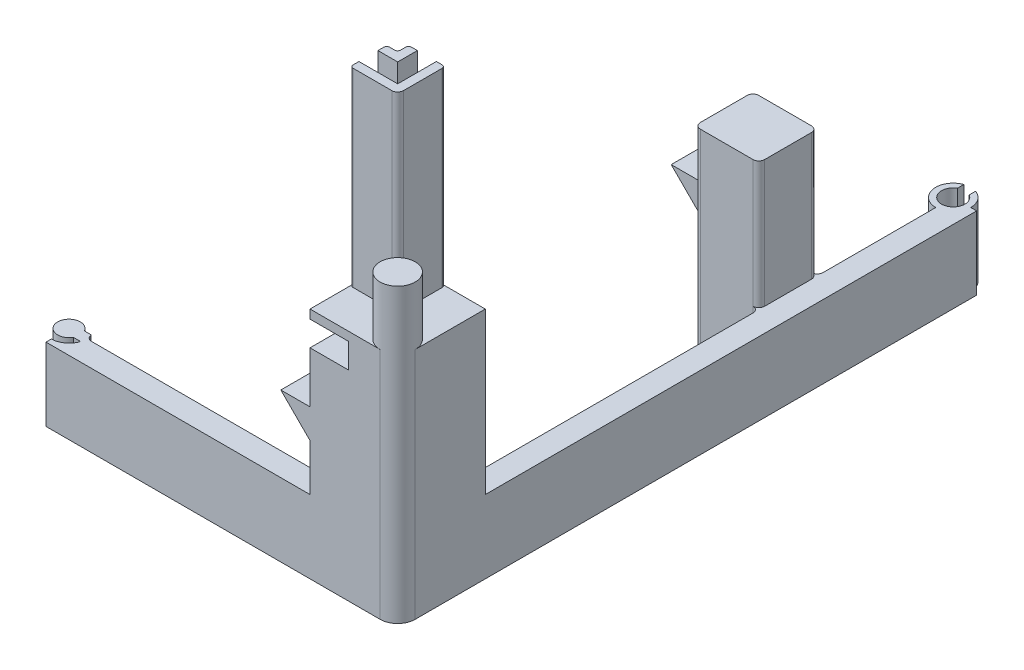
SolidWorks part; units mm, degrees
ref_plane "Front Plane" through (0, 0, 0) normal (0, 0, 1) x (1, 0, 0)
ref_plane "Top Plane" through (0, 0, 0) normal (0, 1, 0) x (1, 0, 0)
ref_plane "Right Plane" through (0, 0, 0) normal (1, 0, 0) x (0, 0, -1)
sketch "Sketch1" plane through (0, 0, 0) normal (0, 1, 0) x (1, 0, 0)
  line L1 (-15, -15) -> (15, -15)
  line L2 (-15, -15) -> (-15, 15)
  line L3 (-15, 15) -> (15, 15)
  line L4 (15, -15) -> (15, 15)
  line L5 (-15, -15) -> (15, 15) construction
  line L6 (-15, 15) -> (15, -15) construction
  point P0 (0, 0)
  dimension "D1" = 30
extrude "Boss-Extrude1" add sketch "Sketch1" along normal blind 80
sketch "Sketch2" plane through (0, 80, 0) normal (0, 1, 0) x (1, 0, 0)
  line L0 (-15, -15) -> (15, -15) construction
  line L1 (15, -15) -> (15, 15) construction
  circle A0 centre (9, -9) radius 6
  dimension "D1" = 12
extrude "Boss-Extrude2" add sketch "Sketch2" along normal blind 20
sketch "Sketch3" plane through (0, 80, 0) normal (0, 1, 0) x (1, 0, 0)
  line L2 (9, -15) -> (15, -15)
  line L4 (15, -15) -> (15, -9)
  circle A1 centre (9, -9) radius 6
  arc A4 (9, -15) -> (15, -9) centre (9, -9) ccw
  dimension "D1" = 0
extrude "Cut-Extrude1" cut sketch "Sketch3" against normal through all
sketch "Sketch4" plane through (0, 80, 0) normal (0, 1, 0) x (1, 0, 0)
  line L16 (-11.25, 1.75) -> (-1.75, 1.75)
  line L17 (-11.25, 11.25) -> (-8.25, 11.25) construction
  line L19 (-11.25, 11.25) -> (-11.25, 8.25) construction
  line L20 (-11.25, 8.25) -> (-8.25, 8.25)
  line L21 (-8.25, 11.25) -> (-8.25, 8.25)
  line L23 (-1.75, 1.75) -> (-1.75, 11.25)
  line L25 (-1.75, 11.25) -> (1.25, 11.25) construction
  line L26 (1.25, 11.25) -> (1.25, -1.25)
  line L27 (1.25, -1.25) -> (-11.25, -1.25)
  line L28 (-11.25, -1.25) -> (-11.25, 1.75) construction
  line L29 (-11.25, 1.75) -> (-11.25, 8.25) construction
  line L30 (-8.25, 11.25) -> (-1.75, 11.25) construction
  line L31 (-11.25, 11.25) -> (-11.25, 15) construction
  line L32 (15, 15) -> (-15, 15) construction
  line L33 (-11.25, 11.25) -> (-15, 11.25) construction
  line L34 (-15, 15) -> (-15, -15) construction
  line L35 (1.25, 11.25) -> (1.25, 15)
  line L36 (1.25, 15) -> (-1.75, 15)
  line L37 (-1.75, 15) -> (-1.75, 11.25)
  line L38 (-11.25, 1.75) -> (-15, 1.75)
  line L39 (-15, 1.75) -> (-15, -1.25)
  line L40 (-15, -1.25) -> (-11.25, -1.25)
  line L41 (-8.25, 11.25) -> (-8.25, 15)
  line L42 (-8.25, 15) -> (-11.25, 15)
  line L43 (-11.25, 15) -> (-11.25, 11.25)
  line L44 (-15, 11.25) -> (-15, 8.25)
  line L45 (-15, 8.25) -> (-11.25, 8.25)
  line L46 (-11.25, 11.25) -> (-15, 11.25)
  dimension "D1" = 6.5
  dimension "D2" = 3
  dimension "D3" = 3.75
extrude "Boss-Extrude3" add sketch "Sketch4" along normal blind 65
sketch "Sketch6" plane through (0, 0, 0) normal (0, -1, 0) x (1, 0, 0)
  line L1 (15, -15) -> (7, -15)
  line L2 (15, -15) -> (15, -183.175)
  line L3 (15, -183.175) -> (13, -183.175)
  line L4 (7, -15) -> (7, -177.175)
  arc A1 (7, -177.175) -> (13, -183.175) centre (7, -183.175) ccw
  dimension "D3" = 12
  dimension "D1" = 168.175
  dimension "D2" = 8
extrude "Boss-Extrude5" add sketch "Sketch6" against normal blind 2
sketch "Sketch7" plane through (0, 2, 0) normal (0, 1, 0) x (1, 0, 0)
  line L0 (7, 187.175) -> (7, 189.175) construction
  line L1 (9, 188.8319) -> (9, 186.6391)
  line L2 (5, 188.8319) -> (5, 186.6391)
  line L3 (7, 179.175) -> (7, 177.175) construction
  line L4 (15, 183.175) -> (13, 183.175)
  line L5 (15, 183.175) -> (15, 15)
  line L6 (15, 15) -> (7, 15)
  line L7 (7, 15) -> (7, 177.175) construction
  line L8 (15, 15) -> (1.25, 15) construction
  line L9 (7, 15) -> (7, 177.175)
  arc A0 (5, 188.8319) -> (7, 177.175) centre (7, 183.175) ccw
  arc A1 (13, 183.175) -> (7, 177.175) centre (7, 183.175) ccw construction
  arc A2 (5, 186.6391) -> (9, 186.6391) centre (7, 183.175) ccw
  arc A3 (13, 183.175) -> (9, 188.8319) centre (7, 183.175) ccw
  dimension "D1" = 2
  dimension "D2" = 2
extrude "Boss-Extrude6" add sketch "Sketch7" along normal offset from surface (23 mm away) 25 up to face at (3.75, 0, -67.5656)
sketch "Sketch9" plane through (0, 0, 0) normal (0, -1, 0) x (1, 0, 0)
  line L0 (15, -15) -> (7, -15) construction
  line L1 (-15, 15) -> (-105.5, 15) construction
  line L2 (-15, 15) -> (-15, 7)
  line L3 (-15, 7) -> (-99.5, 7) construction
  line L4 (-105.5, 15) -> (-105.5, 13.1746) construction
  line L5 (-109.375, 7) -> (-109.5, 7) construction
  line L6 (-101.5, 7) -> (-99.5, 7) construction
  line L7 (-99.5, 9) -> (-102.181, 9) construction
  line L8 (7, -187.175) -> (7, -189.175) construction
  line L9 (9, -188.8319) -> (5, -188.8319) construction
  line L10 (-99.5, 5) -> (-102.181, 5) construction
  line L11 (-99.5, 9) -> (-99.5, 5) construction
  line L12 (-102.1228, 8.9) -> (-99.625, 8.9)
  line L13 (-102.1228, 5.1) -> (-99.5, 5.1) construction
  line L14 (-99.5, 5.1) -> (-99.5, 7) construction
  line L15 (-99.5, 8.9) -> (-99.625, 8.9) construction
  line L16 (-105.375, 15) -> (-105.375, 13.1733)
  line L17 (-105.375, 14.0867) -> (-105.5, 14.0873) construction
  line L18 (-105.375, 15) -> (-15, 15)
  line L19 (-99.5, 5.1) -> (-99.5, 7) construction
  line L20 (-15, 7) -> (-99.5, 7)
  line L21 (-99.8088, 5.1) -> (-102.1228, 5.1)
  circle A0 centre (-105.5, 7) radius 4 construction
  arc A1 (9, -186.6391) -> (5, -186.6391) centre (7, -183.175) ccw construction
  arc A2 (-102.1228, 8.9) -> (-102.1228, 5.1) centre (-105.5, 7) ccw
  arc A4 (-99.625, 8.9) -> (-105.5, 13.1746) centre (-105.5, 7) ccw construction
  arc A6 (-99.625, 8.9) -> (-105.375, 13.1733) centre (-105.5, 7) ccw
  arc A7 (-99.8088, 5.1) -> (-99.5, 7) centre (-105.5, 7) ccw
  arc A8 (7, -177.175) -> (5, -188.8319) centre (7, -183.175) ccw construction
  dimension "D1" = 90.5
  dimension "D2" = 0.125
  dimension "D3" = 1.9
extrude "Boss-Extrude7" add sketch "Sketch9" against normal blind 25
fillet "Fillet1" radius 2 1 edges at (-99.5, 12.5, 7)
sketch "Sketch11" plane through (0, 0, 0) normal (0, -1, 0) x (1, 0, 0)
  line L0 (-99.625, 8.9) -> (-99.75, 8.9) construction
  line L2 (-99.625, 8.9) -> (-102.1228, 8.9) construction
  line L3 (-109.375, 7) -> (-109.5, 7) construction
  circle A0 centre (-105.5, 7) radius 6.0558
  arc A5 (-102.1228, 8.9) -> (-102.1228, 5.1) centre (-105.5, 7) ccw construction
extrude "Cut-Extrude2" cut sketch "Sketch11" against normal offset from surface (2.125 mm away) 0.125 up to face at (7, 2, -185.9552) offset beyond the face yes
sketch "Sketch13" plane through (0, 0, 15) normal (0, 0, 1) x (1, 0, 0)
  line L0 (-15, 80) -> (-15, 25) construction
  line L1 (-15, 68.5) -> (-1.75, 68.5)
  line L2 (-15, 68.5) -> (-15, 77)
  line L3 (-15, 77) -> (-1.75, 77)
  line L4 (-1.75, 68.5) -> (-1.75, 77)
  line L7 (-15, 80) -> (9, 80) construction
  line L9 (-1.75, 145) -> (-1.75, 80) construction
  dimension "D1" = 3
  dimension "D2" = 8.5
extrude "Cut-Extrude4" cut sketch "Sketch13" against normal through all both and the other way through all
sketch "Sketch14" plane through (15, 0, 0) normal (1, 0, 0) x (0, 0, -1)
  line L0 (189.175, 0) -> (-15, 0) construction
fillet "Fillet2" radius 2 1 edges at (1.25, 112.5, 1.25)
sketch "Sketch16" plane through (0, 80, 0) normal (0, 1, 0) x (1, 0, 0)
  line L4 (-15, 11.25) -> (-11.25, 11.25)
  line L5 (-11.25, 11.25) -> (-11.25, 15)
  line L6 (-11.25, 15) -> (-15, 15)
  line L7 (-15, 15) -> (-15, 11.25)
  line L8 (-15, 11.25) -> (-11.25, 11.25)
  line L9 (-11.25, 11.25) -> (-11.25, 15)
  line L10 (-11.25, 15) -> (-15, 15)
  line L11 (-15, 15) -> (-15, 11.25)
  dimension "D1" = 0
extrude "Cut-Extrude6" cut sketch "Sketch16" against normal up to next
fillet "Fillet4" radius 1 5 edges at (-11.25, 111, -15) (-11.25, 111, -11.25) (-15, 111, -11.25) (-15, 112.5, 1.25) (1.25, 112.5, -15)
sketch "Sketch17" plane through (0, 0, 0) normal (0, -1, 0) x (1, 0, 0)
  line L0 (7, -15) -> (7, -177.175) construction
  line L1 (7, -116.6313) -> (-15, -116.6313)
  line L2 (7, -116.6313) -> (7, -136.6313)
  line L3 (7, -136.6313) -> (-15, -136.6313)
  line L4 (-15, -116.6313) -> (-15, -136.6313)
  line L5 (-15, -15) -> (-15, 7) construction
  line L6 (7, -177.175) -> (7, -96.0875) construction
  arc A0 (7, -177.175) -> (13, -183.175) centre (7, -183.175) ccw construction
  point P13 (7, -136.6313)
  dimension "D1" = 20
extrude "Boss-Extrude8" add sketch "Sketch17" against normal up to surface (68.5 mm away) up to face at (-8.375, 68.5, 0)
sketch "Sketch18" plane through (0, 0, 0) normal (0, -1, 0) x (1, 0, 0)
  line L0 (-4, -119.1313) -> (-4, -116.6313) construction
  line L1 (-12.5, -119.1313) -> (4.5, -119.1313)
  line L2 (-12.5, -119.1313) -> (-12.5, -134.1313)
  line L3 (-12.5, -134.1313) -> (4.5, -134.1313)
  line L4 (4.5, -119.1313) -> (4.5, -134.1313)
  line L5 (7, -116.6313) -> (-15, -116.6313) construction
  line L7 (4.5, -126.6313) -> (7, -126.6313) construction
  line L8 (7, -116.6313) -> (7, -136.6313) construction
  dimension "D1" = 2.5
extrude "Cut-Extrude7" cut sketch "Sketch18" against normal offset from surface (66 mm away) 2.5 up to face at (-4, 68.5, -126.6313)
fillet "Fillet5" radius 2 4 edges at (7, 12.5, -116.6313) (7, 12.5, -136.6313) (-15, 34.25, -136.6313) (-15, 34.25, -116.6313)
fillet "Fillet6" radius 2 2 edges at (7, 46.75, -116.6313) (7, 46.75, -136.6313)
chamfer "Chamfer1" distance 7 angle 45 4 edges at (-4, 66, -119.1313) (4.5, 66, -126.6313) (-4, 66, -134.1313) (-12.5, 66, -126.6313)
sketch "Sketch19" plane through (0, 0, 15) normal (0, 0, 1) x (1, 0, 0)
  line L0 (-15, 51) -> (-25, 51)
  line L1 (-15, 68.5) -> (-15, 25) construction
  line L2 (-25, 51) -> (-15, 41)
  line L3 (-15, 41) -> (-15, 51)
  line L4 (-1.75, 68.5) -> (-15, 68.5) construction
  dimension "D1" = 17.5
  dimension "D2" = 10
extrude "Boss-Extrude9" add sketch "Sketch19" against normal up to surface (30 mm away) up to face at (-1.8437, 77.5625, -15)
ref_plane "Plane1" through (0, 0, -126.6313) normal (0, 0, -1) x (-1, 0, 0)
sketch "Sketch20" plane through (0, 0, -126.6313) normal (0, 0, -1) x (-1, 0, 0)
  line L3 (25, 51) -> (15, 51)
  line L4 (15, 41) -> (25, 51)
  line L5 (15, 51) -> (15, 41)
  line L6 (25, 51) -> (15, 51)
  line L7 (15, 41) -> (25, 51)
  line L8 (15, 51) -> (15, 41)
  dimension "D1" = 0
extrude "Boss-Extrude10" add sketch "Sketch20" against normal up to vertex (8 mm away) and the other way up to vertex (8 mm away) up to point (-15, 68.5, -118.6312) other way up to point (-15, 68.5, -134.6312)
